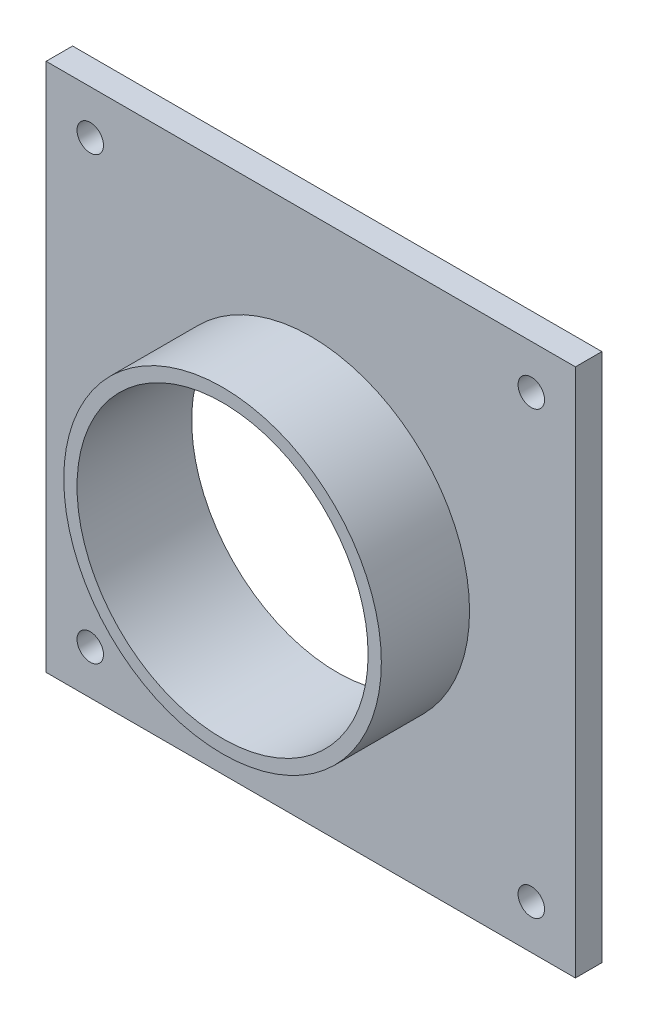
SolidWorks part; units mm, degrees
ref_plane "Front Plane" through (0, 0, 0) normal (0, 0, 1) x (1, 0, 0)
ref_plane "Top Plane" through (0, 0, 0) normal (0, 1, 0) x (1, 0, 0)
ref_plane "Right Plane" through (0, 0, 0) normal (1, 0, 0) x (0, 0, -1)
sketch "Sketch1" plane through (0, 0, 0) normal (0, 0, 1) x (1, 0, 0)
  line L0 (0, 0) -> (60, 0)
  line L1 (60, 0) -> (60, 60)
  line L2 (60, 60) -> (0, 60)
  line L3 (0, 60) -> (0, 0)
  line L4 (30, 60) -> (30, 0) construction
  line L5 (0, 30) -> (60, 30) construction
  circle A0 centre (30, 30) radius 16.5
  circle A1 centre (5, 55) radius 1.5
  circle A2 centre (55, 55) radius 1.5
  circle A3 centre (55, 5) radius 1.5
  circle A4 centre (5, 5) radius 1.5
  point P8 (0, 30)
  point P10 (30, 60)
  dimension "D3" = 33
  dimension "D4" = 3
  dimension "D1" = 60
  dimension "D2" = 60
  dimension "D5" = 50
  dimension "D6" = 50
extrude "Boss-Extrude1" add sketch "Sketch1" along normal blind 3
sketch "Sketch2" plane through (0, 0, 3) normal (0, 0, 1) x (1, 0, 0)
  circle A0 centre (30, 30) radius 16.5
  circle A1 centre (30, 30) radius 18
  dimension "D1" = 36
extrude "Boss-Extrude2" add sketch "Sketch2" along normal blind 10
